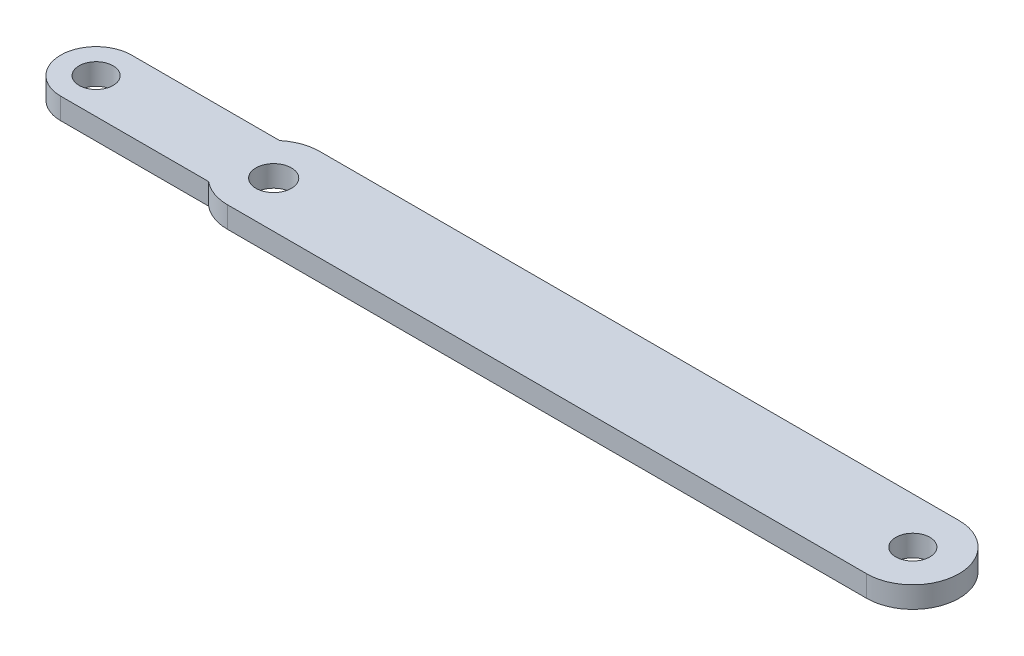
SolidWorks part; units mm, degrees
ref_plane "Front Plane" through (0, 0, 0) normal (0, 0, 1) x (1, 0, 0)
ref_plane "Top Plane" through (0, 0, 0) normal (0, 1, 0) x (1, 0, 0)
ref_plane "Right Plane" through (0, 0, 0) normal (1, 0, 0) x (0, 0, -1)
sketch "Sketch2" plane through (0, 0, 0) normal (0, 1, 0) x (1, 0, 0)
  line L1 (-2.4064, 198.8185) -> (87.5936, 198.8185)
  line L3 (-2.4064, 185.8185) -> (87.5936, 185.8185)
  line L4 (-2.4064, 187.3185) -> (-27.4064, 187.3185)
  line L6 (-2.4064, 197.3185) -> (-27.4064, 197.3185)
  arc A0 (87.5936, 198.8185) -> (87.5936, 185.8185) centre (87.5936, 192.3185) cw
  circle A1 centre (87.5936, 192.3185) radius 2.4
  arc A2 (-2.4064, 198.8185) -> (-2.4064, 185.8185) centre (-2.4064, 192.3185) ccw
  arc A3 (-27.4064, 197.3185) -> (-27.4064, 187.3185) centre (-27.4064, 192.3185) ccw
  circle A4 centre (-27.4064, 192.3185) radius 2.4
  circle A5 centre (-2.4064, 192.3185) radius 2.5
  dimension "D3" = 4.8
  dimension "D7" = 4.8
  dimension "D8" = 5
  dimension "D1" = 90
  dimension "D2" = 13
  dimension "D4" = 1.5
  dimension "D5" = 1.5
  dimension "D6" = 25
extrude "Boss-Extrude1" add sketch "Sketch2" along normal blind 3
